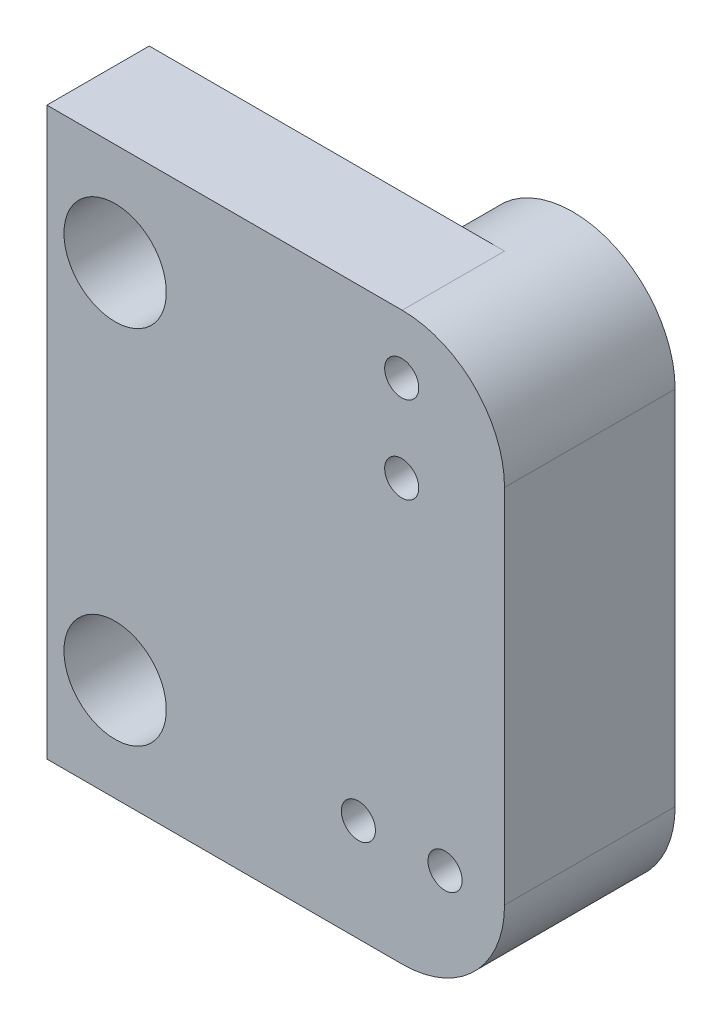
SolidWorks part; units mm, degrees
ref_plane "Front Plane" through (0, 0, 0) normal (0, 0, 1) x (1, 0, 0)
ref_plane "Top Plane" through (0, 0, 0) normal (0, 1, 0) x (1, 0, 0)
ref_plane "Right Plane" through (0, 0, 0) normal (1, 0, 0) x (0, 0, -1)
sketch "Sketch1" plane through (0, 0, -3.2899) normal (0, 0, -1) x (-1, 0, 0)
  line L0 (5.1256, 8.2745) -> (5.1256, 18.8745) construction
  line L1 (2.1256, 8.2745) -> (2.1256, 18.8745)
  line L2 (8.1256, 8.2745) -> (8.1256, 18.8745)
  arc A0 (2.1256, 8.2745) -> (8.1256, 8.2745) centre (5.1256, 8.2745) ccw
  arc A1 (8.1256, 18.8745) -> (2.1256, 18.8745) centre (5.1256, 18.8745) ccw
  circle A2 centre (5.1256, 18.8745) radius 2.5
  circle A3 centre (5.1256, 8.2745) radius 2.5
  point P2 (5.1256, 13.5745)
  dimension "D1" = 3
  dimension "D2" = 5
  dimension "D3" = 5
extrude "Boss-Extrude1" add sketch "Sketch1" along normal blind 5
sketch "Sketch2" plane through (0, 0, -3.2899) normal (0, 0, -1) x (-1, 0, 0)
  circle A0 centre (5.1391, 8.2745) radius 2.5135
  circle A1 centre (5.1391, 18.8745) radius 2.5135
extrude "Boss-Extrude2" add sketch "Sketch2" along normal blind 1
sketch "Sketch4" plane through (0, 0, -3.2899) normal (0, 0, -1) x (-1, 0, 0)
  line L1 (5.1256, 21.8745) -> (-10.4609, 21.8745)
  line L2 (5.1256, 5.2745) -> (-10.4609, 5.2745)
  line L3 (-10.4609, 21.8745) -> (-10.4609, 5.2745)
  line L5 (5.1256, 21.8745) -> (15.5391, 21.8745)
  line L6 (5.1256, 5.2745) -> (15.5391, 5.2745)
  line L7 (15.5391, 21.8745) -> (15.5391, 5.2745)
  line L8 (-6.4609, 23.1745) -> (-6.4609, -2.8255) construction
  line L9 (11.5391, -2.8255) -> (11.5391, 23.1745) construction
  line L10 (5.1391, 18.8745) -> (-10.4609, 18.8745)
  line L11 (5.1391, 18.8745) -> (15.5391, 18.8745)
  line L12 (5.1391, 8.2745) -> (-10.4609, 8.2745)
  line L13 (5.1391, 8.2745) -> (15.5391, 8.2745)
  arc A0 (8.1256, 18.8745) -> (2.1256, 18.8745) centre (5.1256, 18.8745) ccw construction
  arc A1 (2.1256, 8.2745) -> (8.1256, 8.2745) centre (5.1256, 8.2745) ccw construction
  circle A2 centre (-8.4609, 18.8745) radius 1.5
  circle A3 centre (-8.4609, 8.2745) radius 1.5
  circle A4 centre (13.5391, 18.8745) radius 1.5
  circle A5 centre (13.5391, 8.2745) radius 1.5
  dimension "D5" = 3
  dimension "D6" = 3
  dimension "D7" = 3
  dimension "D8" = 3
  dimension "D1" = 4
  dimension "D2" = 4
  dimension "D3" = 2
  dimension "D4" = 2
extrude "Boss-Extrude3" add sketch "Sketch4" along normal blind 3 contours A5 L13 L7 L11 A4 L10 A2 L3 L12 A3 | A4 L11 L7 L5 L1 L3 L10 A2 | A5 L13 L12 A3 L3 L2 L6 L7
sketch "Sketch5" plane through (0, 0, -4.2899) normal (0, 0, -1) x (-1, 0, 0)
  circle A0 centre (5.1391, 20.1445) radius 0.5
  circle A1 centre (5.1391, 17.6045) radius 0.5
  circle A2 centre (3.8691, 8.2745) radius 0.5
  circle A3 centre (6.4091, 8.2745) radius 0.5
extrude "Cut-Extrude1" cut sketch "Sketch5" against normal through all and the other way through all
sketch "Sketch6" plane through (0, 0, -6.2899) normal (0, 0, -1) x (-1, 0, 0)
  line L0 (2.1256, 8.2745) -> (2.1256, 18.8745)
  line L1 (5.1256, 21.8745) -> (-10.4609, 21.8745)
  line L2 (-10.4609, 21.8745) -> (-10.4609, 5.2745)
  line L3 (-10.4609, 5.2745) -> (5.1256, 5.2745)
  circle A0 centre (5.1256, 18.8745) radius 3
  circle A1 centre (5.1256, 8.2745) radius 3
  arc M1 (5.1256, 5.2745) -> (2.1256, 8.2745) centre (5.1256, 8.2745) cw
  line M2 (2.1256, 8.2745) -> (2.1256, 18.8745)
  arc M3 (2.1256, 18.8745) -> (5.1256, 21.8745) centre (5.1256, 18.8745) cw
  line M4 (5.1256, 21.8745) -> (-10.4609, 21.8745)
  line M5 (-10.4609, 21.8745) -> (-10.4609, 5.2745)
  line M6 (-10.4609, 5.2745) -> (5.1256, 5.2745)
  circle M7 centre (-8.4609, 18.8745) radius 1.5
  circle M8 centre (-8.4609, 8.2745) radius 1.5
extrude "Cut-Extrude2" cut sketch "Sketch6" against normal blind 10 contours M6 M1 M2 M3 M4 M5 M7 M8
